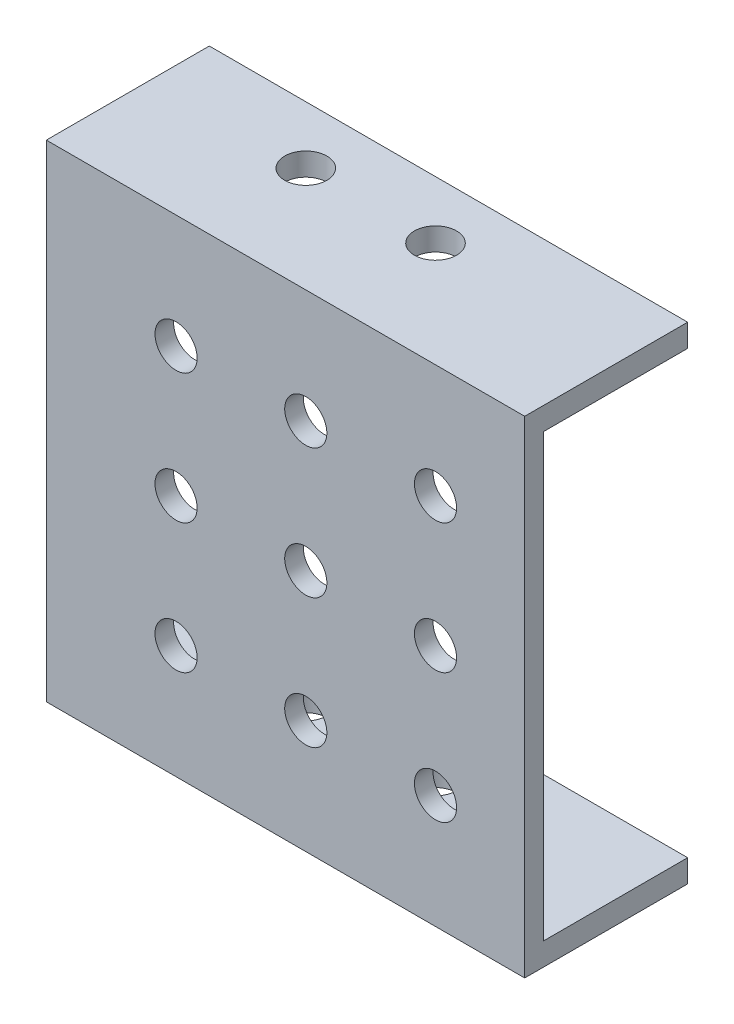
SolidWorks part; units mm, degrees
ref_plane "前视" through (0, 0, 0) normal (0, 0, 1) x (1, 0, 0)
ref_plane "上视" through (0, 0, 0) normal (0, 1, 0) x (1, 0, 0)
ref_plane "右视" through (0, 0, 0) normal (1, 0, 0) x (0, 0, -1)
sketch "草图1" plane through (0, 0, 0) normal (0, 0, 1) x (1, 0, 0)
  line L0 (0, 0) -> (0, 94.429) construction
  line L1 (-147.5, 300) -> (147.5, 300)
  line L2 (-147.5, 300) -> (-147.5, 0)
  line L3 (-147.5, 0) -> (147.5, 0)
  line L4 (147.5, 300) -> (147.5, 0)
  line L5 (-203.17, 70) -> (213.5889, 70) construction
  line L6 (-203.17, 150) -> (228.17, 150) construction
  line L7 (-203.17, 230) -> (213.5889, 230) construction
  line L8 (92.5, -78.7935) -> (92.5, 321.0346) construction
  line L9 (12.5, -78.7935) -> (12.5, 279.3587) construction
  line L10 (-67.5, -78.7935) -> (-67.5, 279.3587) construction
  line L11 (-244.8459, 0) -> (338.6166, 0) construction
  circle A0 centre (92.5, 230) radius 13
  circle A1 centre (92.5, 150) radius 13
  circle A2 centre (92.5, 70) radius 13
  circle A3 centre (12.5, 230) radius 13
  circle A4 centre (-67.5, 230) radius 13
  circle A5 centre (-67.5, 150) radius 13
  circle A6 centre (-67.5, 70) radius 13
  circle A7 centre (12.5, 70) radius 13
  circle A8 centre (12.5, 150) radius 13
  dimension "D9" = 26
  dimension "D10" = 135
  dimension "D1" = 300
  dimension "D2" = 295
  dimension "D3" = 70
  dimension "D4" = 80
  dimension "D5" = 80
  dimension "D6" = 55
  dimension "D7" = 80
  dimension "D8" = 80
extrude "基体-拉伸" add sketch "草图1" along normal blind 11.5
sketch "草图2" plane through (0, 0, 0) normal (0, 0, -1) x (-1, 0, 0)
  line L0 (147.5, 300) -> (147.5, 0) construction
  line L1 (-147.5, 300) -> (147.5, 300)
  line L2 (-147.5, 300) -> (-147.5, 286)
  line L3 (-147.5, 286) -> (147.5, 286)
  line L4 (147.5, 300) -> (147.5, 286)
  line L6 (-147.5, 0) -> (147.5, 0)
  line L7 (-147.5, 0) -> (-147.5, 14)
  line L8 (-147.5, 14) -> (147.5, 14)
  line L9 (147.5, 0) -> (147.5, 14)
  dimension "D1" = 14
  dimension "D2" = 14
extrude "凸台-拉伸1" add sketch "草图2" along normal blind 89
sketch "草图3" plane through (0, 300, 0) normal (0, 1, 0) x (-1, 0, 0)
  line L0 (0, 10.854) -> (0, -103.2512) construction
  line L1 (145.3179, -53.5) -> (-138.666, -53.5) construction
  line L2 (-147.5, 11.5) -> (147.5, 11.5) construction
  line L3 (-147.5, 11.5) -> (-147.5, -89) construction
  circle A0 centre (-27.5, -53.5) radius 13
  circle A1 centre (52.5, -53.5) radius 13
  dimension "D4" = 26
  dimension "D1" = 65
  dimension "D2" = 120
  dimension "D3" = 80
extrude "切除-拉伸1" cut sketch "草图3" against normal through all
